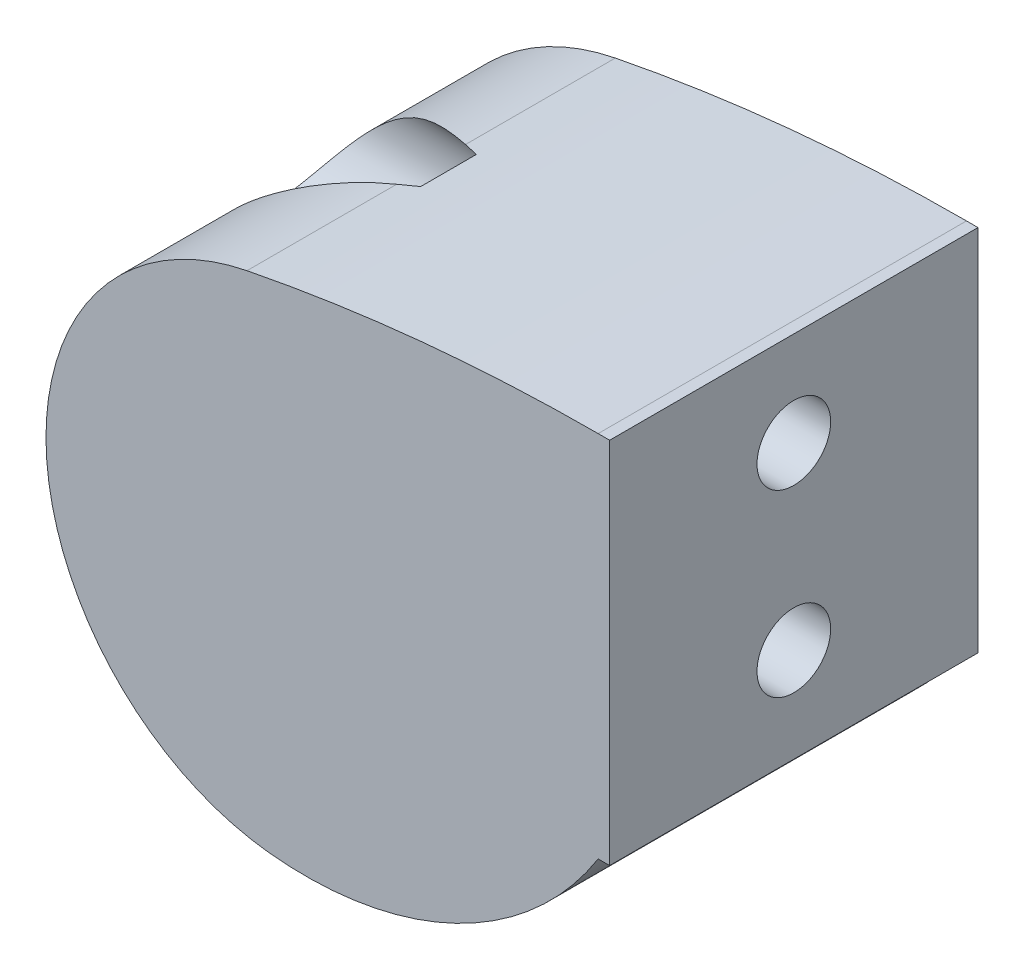
SolidWorks part; units mm, degrees
ref_plane "Front Plane" through (0, 0, 0) normal (0, 0, 1) x (1, 0, 0)
ref_plane "Top Plane" through (0, 0, 0) normal (0, 1, 0) x (1, 0, 0)
ref_plane "Right Plane" through (0, 0, 0) normal (1, 0, 0) x (0, 0, -1)
sketch "Sketch1" plane through (0, 0, 0) normal (0, 0, 1) x (1, 0, 0)
  line L0 (0, 0) -> (13.1886, 0) construction
  line L1 (12.6886, 8) -> (13.1886, 8)
  line L3 (12.6886, -8) -> (13.1886, -8)
  line L4 (13.1886, 8) -> (13.1886, -8)
  arc A0 (12.6886, 8) -> (12.6886, -8) centre (0, 0) ccw
  dimension "D1" = 30
  dimension "D2" = 0.5
  dimension "D3" = 16
extrude "Boss-Extrude1" add sketch "Sketch1" along normal blind 16
sketch "Sketch2" plane through (0, 0, 16) normal (0, 0, 1) x (1, 0, 0)
  line L0 (13.1886, 8) -> (12.6886, 8) construction
  line L1 (-1.6387, -14.9102) -> (-1.6387, -32.4173)
  line L2 (-1.6387, -32.4173) -> (-50.7655, -32.4173)
  line L3 (-50.7655, -32.4173) -> (-50.7655, 31.2395)
  line L4 (-50.7655, 31.2395) -> (12.6886, 31.2395)
  line L5 (12.6886, 31.2395) -> (12.6886, 8)
  arc A0 (12.6886, 8) -> (-2.566, 6.4999) centre (12.6886, -70.315) ccw
  arc A1 (12.6886, 8) -> (12.6886, -8) centre (0, 0) ccw construction
  arc A2 (-1.6387, -14.9102) -> (-2.566, 6.4999) centre (-0.4543, -4.1338) cw
extrude "Cut-Extrude1" cut sketch "Sketch2" against normal through all
sketch "Sketch3" plane through (13.1886, 0, 0) normal (1, 0, 0) x (0, 0, -1)
  circle A0 centre (-8, -3.9) radius 2.85 construction
  circle A1 centre (-8, -3.9) radius 2.85 construction
  circle A2 centre (-8, 3.9) radius 2.85 construction
  circle A3 centre (-8, 3.9) radius 2.85 construction
  circle A4 centre (-8, 3.9) radius 1.6
  circle A5 centre (-8, -3.9) radius 1.6
  dimension "D2" = 3.2
extrude "Cut-Extrude2" cut sketch "Sketch3" against normal through all
ref_plane "Plane1" through (-1.8114, 0, 0) normal (1, 0, 0) x (0, 0, -1)
sketch "Sketch4" plane through (-1.8114, 0, 0) normal (1, 0, 0) x (0, 0, -1)
  circle A0 centre (-8, 3.9) radius 3
  circle A1 centre (-8, -3.9) radius 3
  dimension "D1" = 6
extrude "Cut-Extrude3" cut sketch "Sketch4" against normal through all
